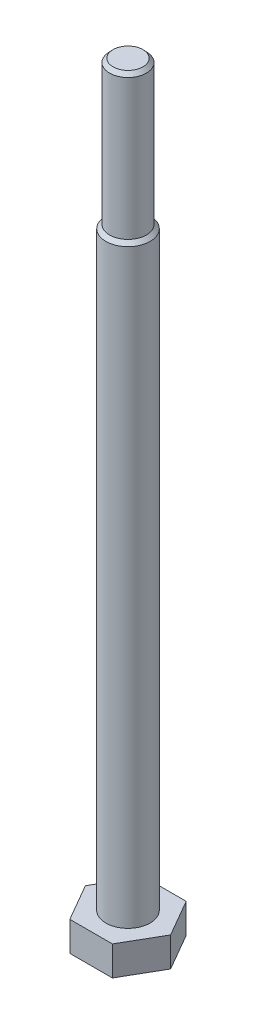
SolidWorks part; units mm, degrees
ref_plane "Ön Düzlem" through (0, 0, 0) normal (0, 0, 1) x (1, 0, 0)
ref_plane "Üst Düzlem" through (0, 0, 0) normal (0, 1, 0) x (1, 0, 0)
ref_plane "Sağ Düzlem" through (0, 0, 0) normal (1, 0, 0) x (0, 0, -1)
sketch "Çizim2" plane through (0, 0, 0) normal (0, 1, 0) x (1, 0, 0)
  line L7 (5.7735, 0) -> (2.8868, 5)
  line L8 (2.8868, 5) -> (-2.8868, 5)
  line L9 (-2.8868, 5) -> (-5.7735, 0)
  line L10 (-5.7735, 0) -> (-2.8868, -5)
  line L11 (-2.8868, -5) -> (2.8868, -5)
  line L12 (2.8868, -5) -> (5.7735, 0)
  circle A0 centre (0, 0) radius 5 construction
  dimension "D1" = 10
extrude "Yükseklik-Ekstrüzyon1" add sketch "Çizim2" along normal blind 4
sketch "Çizim3" plane through (0, 4, 0) normal (0, 1, 0) x (1, 0, 0)
  circle A0 centre (0, 0) radius 3
  dimension "D1" = 6
extrude "Yükseklik-Ekstrüzyon2" add sketch "Çizim3" along normal blind 100
sketch "Çizim4" plane through (0, 0, 0) normal (0, 0, 1) x (1, 0, 0)
  line L0 (0, 106.3109) -> (0, 75.6114) construction
  line L1 (-2.5, 103.5) -> (-2.5, 84.5)
  line L2 (-3, 84) -> (-5.565, 84)
  line L3 (-5.565, 84) -> (-5.565, 104)
  line L4 (-5.565, 104) -> (-2.5, 104)
  line L5 (3, 104) -> (-3, 104) construction
  line L6 (-3, 104) -> (-3, 4) construction
  line L7 (-2.5, 84.5) -> (-3, 84)
  line L8 (-2.5, 103.5) -> (-2.027, 104)
  line L9 (-2.027, 104) -> (-2.5, 104)
  point P4 (-2.5, 84)
  dimension "D1" = 20
  dimension "D2" = 0.5
  dimension "D3" = 0.5
revolve "Kes-Döndür1" cut sketch "Çizim4" angle 360 about L0
